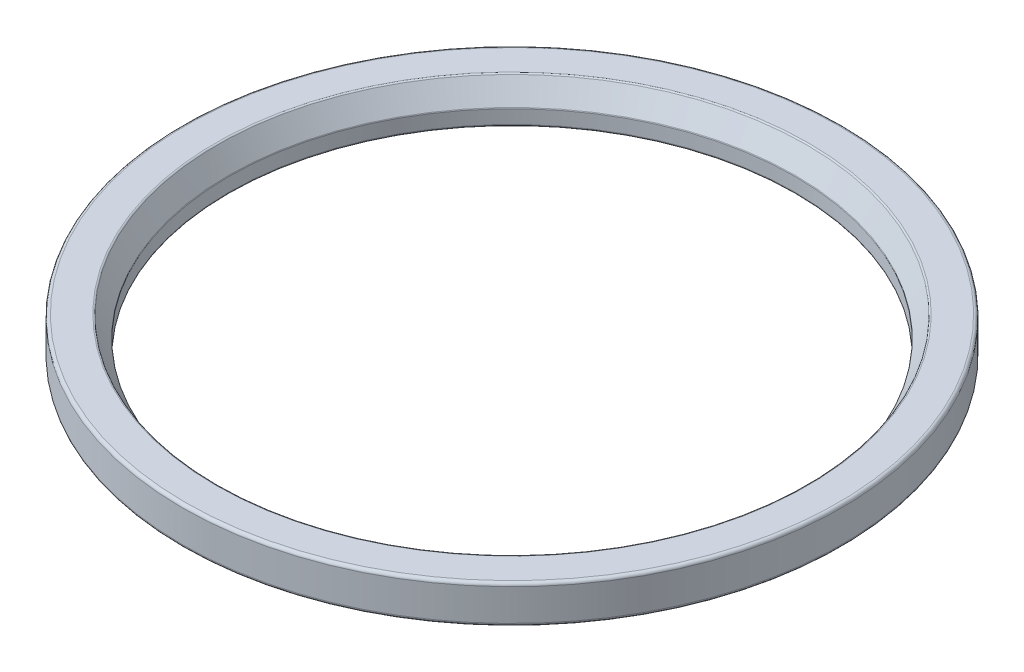
SolidWorks part; units mm, degrees
ref_plane "Plano frontal" through (0, 0, 0) normal (0, 0, 1) x (1, 0, 0)
ref_plane "Plano superior" through (0, 0, 0) normal (0, 1, 0) x (1, 0, 0)
ref_plane "Plano direito" through (0, 0, 0) normal (1, 0, 0) x (0, 0, -1)
sketch "Esboço1" plane through (0, 0, 0) normal (0, 0, 1) x (1, 0, 0)
  line L0 (0, -41.542) -> (0, 47.7815) construction
  line L1 (45.5, 6.8593) -> (45.5, 9.3593)
  line L2 (45.5, 9.3593) -> (47.5, 12.8593)
  line L3 (47.5, 12.8593) -> (53, 12.8593)
  line L4 (53, 12.8593) -> (53, 6.8593)
  arc A0 (45.5, 6.8593) -> (53, 6.8593) centre (49.25, 20.8273) ccw
  dimension "D1" = 45.5
  dimension "D2" = 47.5
  dimension "D3" = 2.5
  dimension "D4" = 3.5
  dimension "D5" = 53
revolve "Revolução1" add sketch "Esboço1" angle 360 about L0
fillet "Filete1" radius 0.5 2 edges at (0, 6.8593, -53) (0, 12.8593, -53)
fillet "Filete2" radius 0.3 3 edges at (0, 6.8593, -45.5) (0, 9.3593, -45.5) (0, 12.8593, -47.5)
